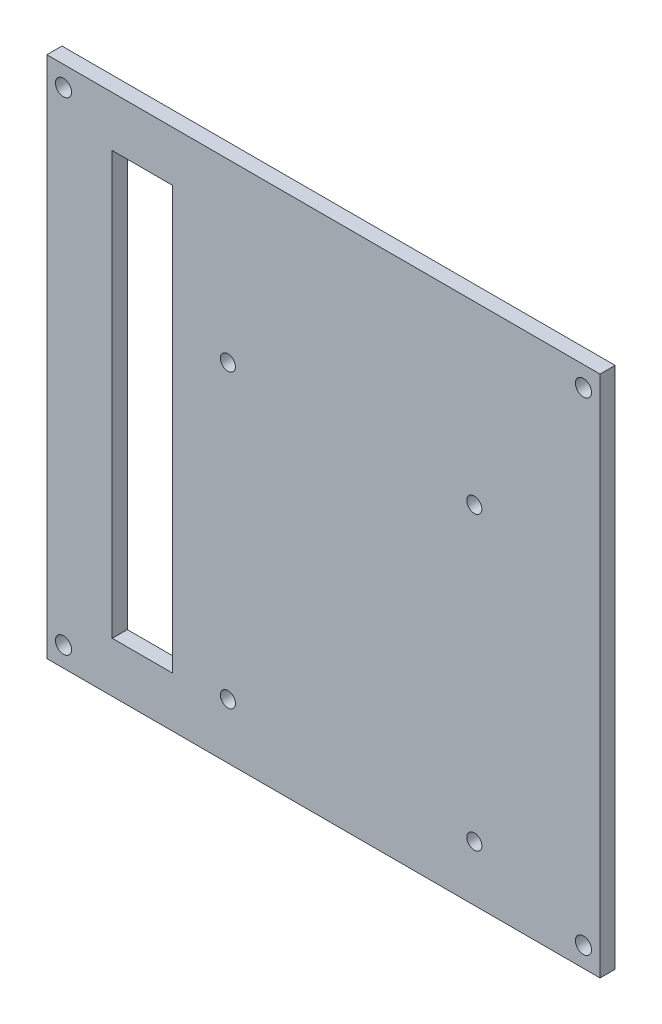
SolidWorks part; units mm, degrees
ref_plane "Alzado" through (0, 0, 0) normal (0, 0, 1) x (1, 0, 0)
ref_plane "Planta" through (0, 0, 0) normal (0, 1, 0) x (1, 0, 0)
ref_plane "Vista lateral" through (0, 0, 0) normal (1, 0, 0) x (0, 0, -1)
sketch "Croquis1" plane through (0, 0, 0) normal (0, 0, 1) x (1, 0, 0)
  line L1 (0, 82) -> (110, 82)
  line L2 (0, 82) -> (0, -10)
  line L3 (0, -10) -> (110, -10)
  line L4 (110, 82) -> (110, -10)
  line L5 (0, 82) -> (110, 82)
  line L9 (0, -10) -> (110, -10)
  dimension "D1" = 110
  dimension "D2" = 92
extrude "Saliente-Extruir1" add sketch "Croquis1" along normal blind 3
sketch "Croquis7" plane through (0, 82, 0) normal (0, 1, 0) x (1, 0, 0)
  line L1 (0, 0) -> (110, 0)
  line L2 (0, 0) -> (0, -3)
  line L3 (0, -3) -> (110, -3)
  line L4 (110, 0) -> (110, -3)
extrude "Saliente-Extruir2" add sketch "Croquis7" along normal blind 6
sketch "Croquis8" plane through (0, -10, 0) normal (0, -1, 0) x (1, 0, 0)
  line L1 (0, 3) -> (110, 3)
  line L2 (0, 3) -> (0, 0)
  line L3 (0, 0) -> (110, 0)
  line L4 (110, 3) -> (110, 0)
extrude "Saliente-Extruir3" add sketch "Croquis8" along normal blind 6
sketch "Croquis9" plane through (0, 0, 3) normal (0, 0, 1) x (1, 0, 0)
  line L1 (110, 88) -> (110, -16) construction
  line L3 (110, -16) -> (0, -16) construction
  circle A0 centre (97.5, -6) radius 2.5
  dimension "D1" = 5
  dimension "D3" = 10
  dimension "D2" = 12.5
sketch "Croquis11" plane through (0, 0, 3) normal (0, 0, 1) x (1, 0, 0)
  line L0 (0, 84) -> (110, 84) construction
  line L1 (0, 88) -> (0, -16) construction
  line L2 (110, 88) -> (110, -16) construction
  line L3 (3.3, 88) -> (3.3, -16) construction
  line L4 (0, 88) -> (110, 88) construction
  line L5 (110, -16) -> (0, -16) construction
  line L6 (106.7, 88) -> (106.7, -16) construction
  line L7 (0, -12) -> (110, -12) construction
  dimension "D1" = 4
  dimension "D2" = 3.3
  dimension "D3" = 3.3
  dimension "D4" = 4
hole_wizard "Taladro de margen para M31" positions "Croquis3D2" profile "Croquis12" hole size "M3" standard "ISO" end condition through all
sketch3d "Croquis3D2"
  line L0 (0, 84, 3) -> (110, 84, 3) construction
  line L1 (3.3, 88, 3) -> (3.3, -16, 3) construction
  line L2 (0, -12, 3) -> (110, -12, 3) construction
  line L3 (106.7, 88, 3) -> (106.7, -16, 3) construction
  point P0 (3.3, 84, 3)
  point P6 (3.3, -12, 3)
  point P10 (106.7, -12, 3)
  point P14 (106.7, 84, 3)
sketch "Croquis12" plane through (3.3, 84, 3) normal (1, 0, 0) x (0, -1, 0)
  line L0 (0, 0) -> (0, 3)
  line L1 (0, 3) -> (1.6, 3)
  line L2 (1.6, 3) -> (1.6, 0)
  line L5 (1.6, 0) -> (0, 0)
  line L11 (0, -6.35) -> (0, 107.95) construction
  dimension "Diámetro de taladro hasta el siguiente" = 3.2
  dimension "Profundidad de taladro hasta el siguiente" = 3
sketch "Croquis13" plane through (0, 0, 3) normal (0, 0, 1) x (1, 0, 0)
  line L0 (36, 88) -> (36, -16) construction
  line L1 (110, -16) -> (0, -16) construction
  line L2 (85, 88) -> (85, -16) construction
  line L3 (55, 88) -> (55, -16) construction
  line L4 (0, 88) -> (0, -16) construction
  line L5 (110, 88) -> (110, -16) construction
  line L6 (0, 88) -> (110, 88) construction
  line L7 (0, 53) -> (110, 53) construction
  circle A0 centre (36, 53) radius 1.5
  circle A1 centre (85, 53) radius 1.5
  circle A2 centre (36, -5) radius 1.5
  circle A3 centre (85, -5) radius 1.5
  dimension "D4" = 3
  dimension "D1" = 19
  dimension "D2" = 49
  dimension "D3" = 58
  dimension "D5" = 11
extrude "Cortar-Extruir2" cut sketch "Croquis13" against normal up to next
sketch "Croquis14" plane through (0, 0, 3) normal (0, 0, 1) x (1, 0, 0)
  line L0 (0, 88) -> (0, -16) construction
  line L1 (13, 78) -> (25, 78)
  line L2 (13, 78) -> (13, -6)
  line L3 (13, -6) -> (25, -6)
  line L4 (25, 78) -> (25, -6)
  line L5 (0, 88) -> (110, 88) construction
  line L6 (110, -16) -> (0, -16) construction
  dimension "D1" = 12
  dimension "D2" = 13
  dimension "D3" = 10
  dimension "D4" = 10
extrude "Cortar-Extruir3" cut sketch "Croquis14" against normal up to next
